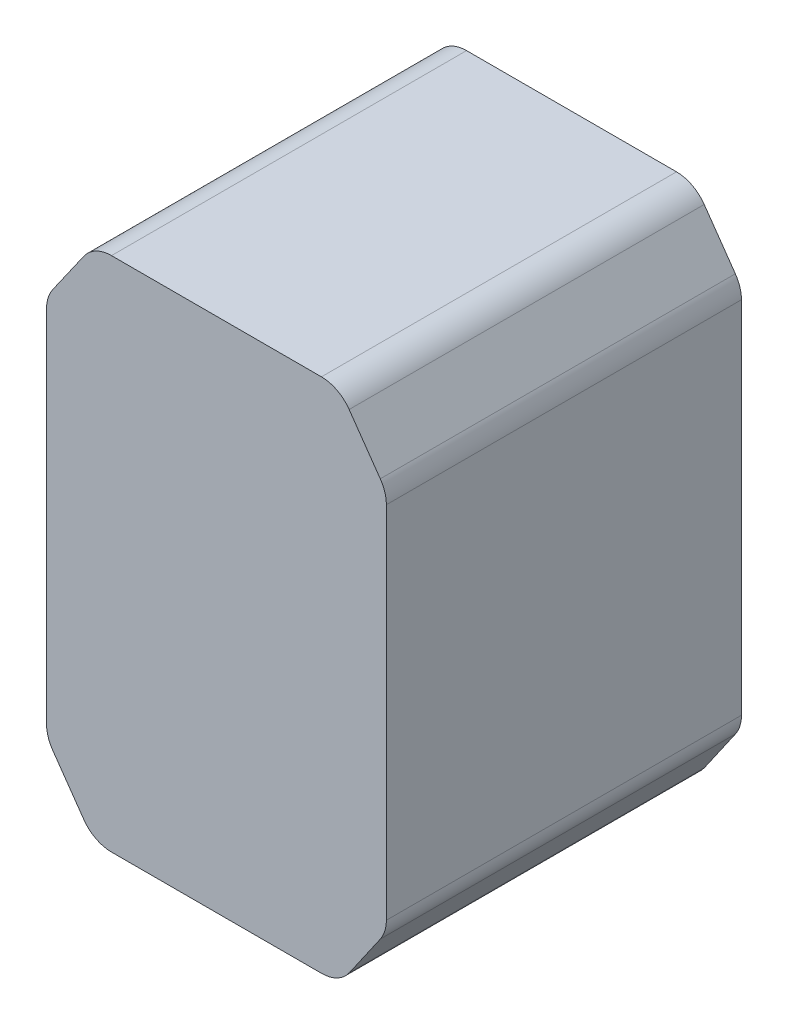
SolidWorks part; units mm, degrees
ref_plane "Front Plane" through (0, 0, 0) normal (0, 0, 1) x (1, 0, 0)
ref_plane "Top Plane" through (0, 0, 0) normal (0, 1, 0) x (1, 0, 0)
ref_plane "Right Plane" through (0, 0, 0) normal (1, 0, 0) x (0, 0, -1)
sketch "Sketch1" plane through (0, 0, 0) normal (0, 0, 1) x (1, 0, 0)
  line L1 (-20.1, -30.55) -> (20.1, -30.55)
  line L2 (-20.1, -30.55) -> (-20.1, 30.55)
  line L3 (-20.1, 30.55) -> (20.1, 30.55)
  line L4 (20.1, -30.55) -> (20.1, 30.55)
  line L5 (-20.1, -30.55) -> (20.1, 30.55) construction
  line L6 (-20.1, 30.55) -> (20.1, -30.55) construction
  point P0 (0, 0)
  dimension "D1" = 40.2
  dimension "D2" = 61.1
extrude "Boss-Extrude1" add sketch "Sketch1" along normal mid plane 42
sketch "Sketch2" plane through (0, 0, 21) normal (0, 0, 1) x (1, 0, 0)
  line L0 (20.1, 0) -> (20.1, -21.2737)
  line L1 (-12.4174, -30.55) -> (12.4395, -30.55)
  line L3 (20.1, -30.55) -> (20.1, 30.55) construction
  line L4 (-12.4174, 30.55) -> (12.4174, 30.55)
  line L5 (20.1, 0) -> (20.1, 21.2891)
  line L7 (-20.1, 0) -> (-20.1, 21.2891)
  line L10 (-20.1, 30.55) -> (-20.1, -30.55) construction
  line L11 (-20.1, 0) -> (-20.1, -21.2891)
  line L13 (-20.1, -30.55) -> (20.1, -30.55) construction
  line L18 (20.1, 30.55) -> (-20.1, 30.55) construction
  line L20 (-19.3769, 23.583) -> (-15.6943, 28.8438)
  line L21 (15.6943, 28.8438) -> (19.3769, 23.583)
  line L22 (-19.3769, -23.583) -> (-15.6943, -28.8438)
  line L23 (15.7261, -28.83) -> (19.3865, -23.5537)
  arc A0 (-15.6943, -28.8438) -> (-12.4174, -30.55) centre (-12.4174, -26.55) ccw
  arc A1 (-20.1, -21.2891) -> (-19.3769, -23.583) centre (-16.1, -21.2891) ccw
  arc A2 (-19.3769, 23.583) -> (-20.1, 21.2891) centre (-16.1, 21.2891) ccw
  arc A3 (-12.4174, 30.55) -> (-15.6943, 28.8438) centre (-12.4174, 26.55) ccw
  arc A4 (15.6943, 28.8438) -> (12.4174, 30.55) centre (12.4174, 26.55) ccw
  arc A5 (20.1, 21.2891) -> (19.3769, 23.583) centre (16.1, 21.2891) ccw
  arc A6 (19.3865, -23.5537) -> (20.1, -21.2737) centre (16.1, -21.2737) ccw
  arc A7 (12.4395, -30.55) -> (15.7261, -28.83) centre (12.4395, -26.55) ccw
  point P10 (20.1, 0)
  point P15 (-20.1, 0)
  point P26 (-14.5, -30.55)
  point P29 (-20.1, -22.55)
  point P32 (-20.1, 22.55)
  point P35 (-14.5, 30.55)
  point P38 (14.5, 30.55)
  point P41 (20.1, 22.55)
  point P44 (20.1, -22.5253)
  point P47 (14.5329, -30.55)
  dimension "D1" = 4
  dimension "D2" = 4
  dimension "D3" = 4
  dimension "D4" = 4
  dimension "D5" = 4
  dimension "D6" = 4
  dimension "D7" = 4
  dimension "D8" = 4
  dimension "D9" = 6.4217
  dimension "D10" = 6.4217
  dimension "D11" = 24.8569
  dimension "D12" = 42.5628
  dimension "D13" = 24.8348
extrude "Cut-Extrude-Thin1" cut sketch "Sketch2" against normal blind 42 thin thin type one direction wall 10
